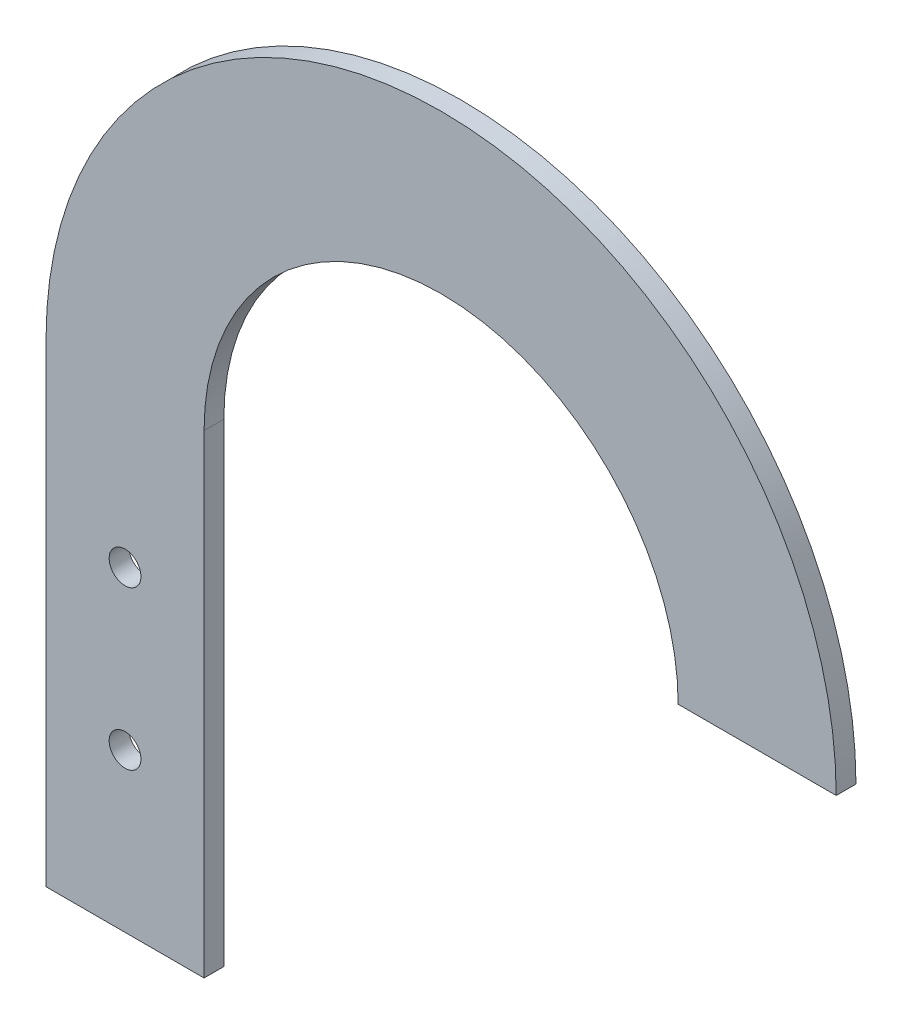
SolidWorks part; units mm, degrees
material "6061 Alloy"
ref_plane "Front" through (0, 0, 0) normal (0, 0, 1) x (1, 0, 0)
ref_plane "Top" through (0, 0, 0) normal (0, 1, 0) x (1, 0, 0)
ref_plane "Right" through (0, 0, 0) normal (1, 0, 0) x (0, 0, -1)
sketch "Sketch1" plane through (0, 0, 0) normal (0, 0, 1) x (1, 0, 0)
  line L0 (0, 0) -> (25.4, 0)
  line L1 (25.4, 0) -> (25.4, 76.2)
  line L2 (0, 0) -> (0, 76.2)
  line L3 (101.6, 76.2) -> (127, 76.2)
  arc A0 (0, 76.2) -> (127, 76.2) centre (63.5, 76.2) cw
  arc A1 (25.4, 76.2) -> (101.6, 76.2) centre (63.5, 76.2) cw
  dimension "D1" = 76.2
  dimension "D3" = 38.1
  dimension "D2" = 25.4
extrude "Boss-Extrude1" add sketch "Sketch1" along normal blind 3.175
hole_wizard "#10 Clearance Hole1" positions "Sketch2" profile "Sketch3" hole size "#10" standard "ANSI Inch"
sketch "Sketch2" plane through (0, 0, 0) normal (0, 0, -1) x (-1, 0, 0)
  line L1 (0, 0) -> (-25.4, 0) construction
  line L2 (-25.4, 0) -> (-25.4, 76.2) construction
  point P0 (-12.7, 25.4)
  point P2 (-12.7, 50.8)
  point P4 (-12.7, 50.8)
  dimension "D1" = 25.4
  dimension "D2" = 25.4
  dimension "D3" = 12.7
sketch "Sketch3" plane through (12.7, 25.4, 0) normal (1, 0, 0) x (0, 1, 0)
  line L0 (0, 0) -> (0, 4.7078)
  line L1 (0, 4.7078) -> (2.5527, 3.174)
  line L2 (2.5527, 3.174) -> (2.5527, 0)
  line L5 (2.5527, 0) -> (0, 0)
  line L10 (0, 4.7078) -> (-2.5527, 3.174) construction
  line L11 (0, -6.35) -> (0, 107.95) construction
  dimension "Hole Dia." = 5.1054
  dimension "Hole Depth" = 3.174
  dimension "Drill Angle" = 118
